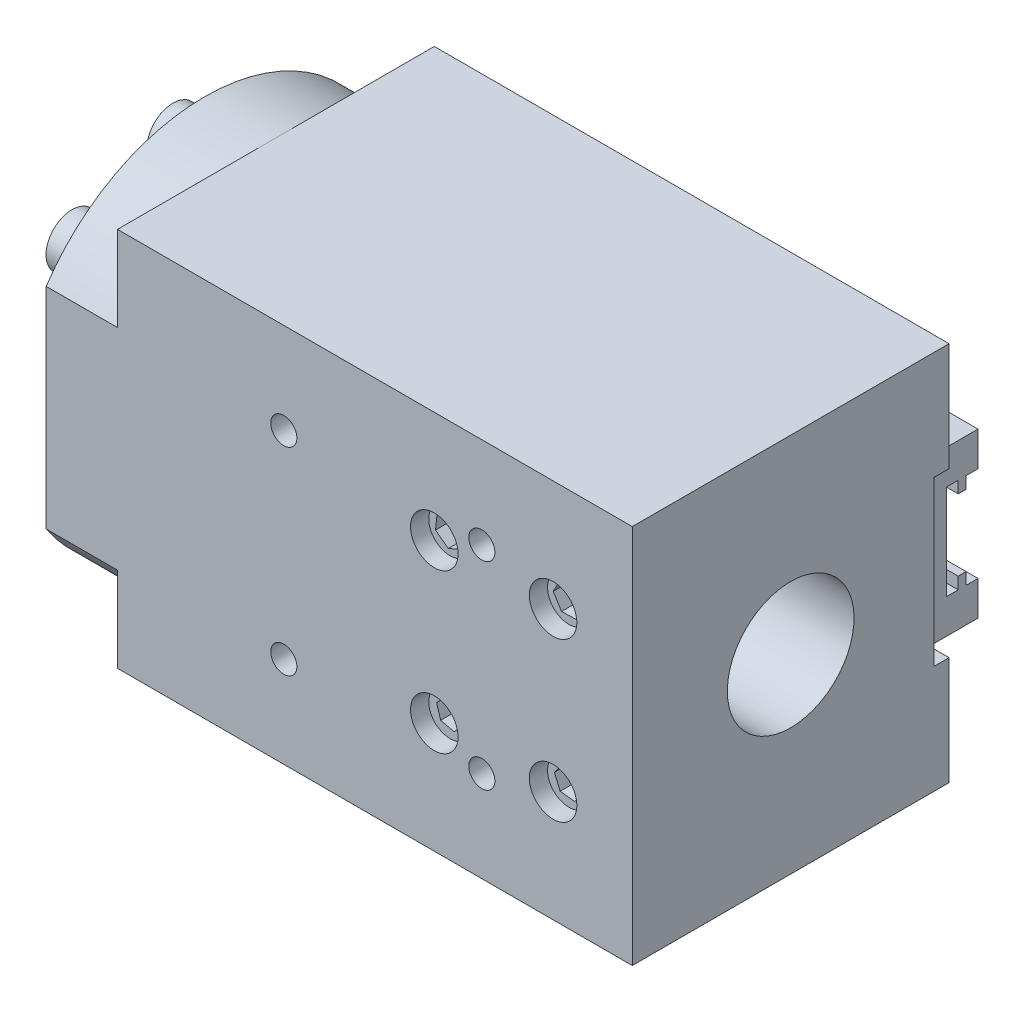
SolidWorks part; units mm, degrees
ref_plane "前视基准面" through (0, 0, 0) normal (0, 0, 1) x (1, 0, 0)
ref_plane "上视基准面" through (0, 0, 0) normal (0, 1, 0) x (1, 0, 0)
ref_plane "右视基准面" through (0, 0, 0) normal (1, 0, 0) x (0, 0, -1)
sketch "草图1" plane through (0, 0, 0) normal (0, 0, 1) x (1, 0, 0)
  line L1 (-32.5, 24) -> (32.5, 24)
  line L2 (-32.5, 24) -> (-32.5, -24)
  line L3 (-32.5, -24) -> (32.5, -24)
  line L4 (32.5, 24) -> (32.5, -24)
  line L5 (-32.5, 24) -> (32.5, -24) construction
  line L6 (-32.5, -24) -> (32.5, 24) construction
  point P0 (0, 0)
  dimension "D1" = 48
  dimension "D2" = 65
extrude "凸台-拉伸1" add sketch "草图1" along normal blind 40
sketch "草图2" plane through (0, 0, 40) normal (0, 0, 1) x (1, 0, 0)
  line L0 (32.5, -24) -> (32.5, 24) construction
  line L1 (32.5, 24) -> (-32.5, 24) construction
  line L2 (-32.5, -24) -> (32.5, -24) construction
  circle A0 centre (22.5, 10) radius 3
  circle A1 centre (22.5, -10) radius 3
  circle A2 centre (7.5, 10) radius 3
  circle A3 centre (7.5, -10) radius 3
  dimension "D1" = 6
  dimension "D2" = 6
  dimension "D3" = 6
  dimension "D4" = 6
  dimension "D5" = 15
  dimension "D6" = 15
  dimension "D7" = 10
  dimension "D8" = 10
  dimension "D9" = 14
  dimension "D10" = 14
  dimension "D11" = 14
  dimension "D12" = 14
extrude "切除-拉伸1" cut sketch "草图2" against normal blind 6
hole_wizard "Ø3.3 (3.3) 直径孔1" positions "草图3" profile "草图4" hole size "Ø3.3" standard "GB"
sketch "草图3" plane through (0, 0, 40) normal (0, 0, 1) x (1, 0, 0)
  line L0 (32.5, -24) -> (32.5, 24) construction
  line L2 (-32.5, -24) -> (32.5, -24) construction
  line L3 (32.5, 24) -> (-32.5, 24) construction
  point P0 (13.5, -12.5)
  point P14 (-11.5, -12.5)
  point P17 (13.5, 12.5)
  point P19 (-11.5, 12.5)
  dimension "D1" = 19
  dimension "D2" = 11.5
  dimension "D3" = 25
  dimension "D4" = 11.5
  dimension "D5" = 11.5
  dimension "D6" = 25
sketch "草图4" plane through (13.5, -12.5, 40) normal (1, 0, 0) x (0, -1, 0)
  line L0 (0, 0) -> (0, 10.9914)
  line L1 (0, 10.9914) -> (1.65, 10)
  line L2 (1.65, 10) -> (1.65, 0)
  line L5 (1.65, 0) -> (0, 0)
  line L10 (0, 10.9914) -> (-1.65, 10) construction
  line L11 (0, -6.35) -> (0, 107.95) construction
  dimension "孔直径" = 3.3
  dimension "孔深度" = 10
  dimension "导头角度" = 118
sketch "草图5" plane through (0, 0, 34) normal (0, 0, 1) x (1, 0, 0)
  circle A0 centre (22.5, 10) radius 2.7
  circle A1 centre (7.5, 10) radius 2.7
  circle A2 centre (7.5, -10) radius 2.7
  circle A3 centre (22.5, -10) radius 2.7
  dimension "D1" = 5.4
  dimension "D2" = 5.4
  dimension "D3" = 5.4
  dimension "D4" = 5.4
extrude "凸台-拉伸2" add sketch "草图5" along normal blind 4
sketch "草图6" plane through (0, 0, 38) normal (0, 0, 1) x (1, 0, 0)
  line L1 (24.3416, -10.211) -> (23.6035, -8.5106)
  line L2 (23.6035, -8.5106) -> (21.7619, -8.2997)
  line L3 (21.7619, -8.2997) -> (20.6584, -9.789)
  line L4 (20.6584, -9.789) -> (21.3965, -11.4894)
  line L5 (21.3965, -11.4894) -> (23.2381, -11.7003)
  line L6 (23.2381, -11.7003) -> (24.3416, -10.211)
  line L7 (5.7948, -9.6064) -> (6.3065, -11.2799)
  line L8 (6.3065, -11.2799) -> (8.0117, -11.6735)
  line L9 (8.0117, -11.6735) -> (9.2052, -10.3936)
  line L10 (9.2052, -10.3936) -> (8.6935, -8.7201)
  line L11 (8.6935, -8.7201) -> (6.9883, -8.3265)
  line L12 (6.9883, -8.3265) -> (5.7948, -9.6064)
  line L13 (21.4504, 11.6821) -> (20.5185, 9.9321)
  line L14 (20.5185, 9.9321) -> (21.5681, 8.25)
  line L15 (21.5681, 8.25) -> (23.5496, 8.3179)
  line L16 (23.5496, 8.3179) -> (24.4815, 10.0679)
  line L17 (24.4815, 10.0679) -> (23.4319, 11.75)
  line L18 (23.4319, 11.75) -> (21.4504, 11.6821)
  line L19 (5.8733, 11.1988) -> (5.6484, 9.1906)
  line L20 (5.6484, 9.1906) -> (7.2752, 7.9918)
  line L21 (7.2752, 7.9918) -> (9.1267, 8.8012)
  line L22 (9.1267, 8.8012) -> (9.3516, 10.8094)
  line L23 (9.3516, 10.8094) -> (7.7248, 12.0082)
  line L24 (7.7248, 12.0082) -> (5.8733, 11.1988)
  circle A0 centre (22.5, -10) radius 1.8536 construction
  circle A1 centre (7.5, -10) radius 1.75 construction
  circle A2 centre (22.5, 10) radius 1.717 construction
  circle A3 centre (7.5, 10) radius 1.75 construction
  dimension "D1" = 3.5
  dimension "D2" = 3.5
extrude "切除-拉伸2" cut sketch "草图6" against normal blind 4
sketch "草图7" plane through (-32.5, 0, 0) normal (-1, 0, 0) x (0, 0, 1)
  line L4 (0, 24) -> (0, -24)
  line L5 (0, -24) -> (40, -24)
  line L6 (40, -24) -> (40, 24)
  line L7 (40, 24) -> (0, 24)
  line L8 (0, 13.2665) -> (0, -13.2665)
  line L10 (40, -13.2665) -> (40, 13.2665)
  arc A0 (40, 13.2665) -> (0, 13.2665) centre (20, 0) ccw
  arc A1 (0, -13.2665) -> (40, -13.2665) centre (20, 0) ccw
  point P4 (0, 0)
  dimension "D1" = 48
  dimension "D3" = 20
  dimension "D2" = 0
extrude "凸台-拉伸3" add sketch "草图7" along normal blind 9
sketch "草图8" plane through (-41.5, 0, 0) normal (-1, 0, 0) x (0, 0, 1)
  line L0 (32.7279, 12.7279) -> (20, 0) construction
  line L1 (20, 18) -> (20, 0) construction
  line L2 (20, 0) -> (7.2721, 12.7279) construction
  circle A0 centre (20, 18) radius 3.3
  circle A1 centre (20, 0) radius 18 construction
  circle A2 centre (32.7279, 12.7279) radius 3.3
  circle A3 centre (7.2721, 12.7279) radius 3.3
  dimension "D1" = 6.6
  dimension "D2" = 36
  dimension "D3" = 6.6
  dimension "D4" = 6.6
  dimension "D5" = 45
  dimension "D6" = 45
extrude "凸台-拉伸4" add sketch "草图8" along normal blind 4
sketch "草图9" plane through (-45.5, 0, 0) normal (-1, 0, 0) x (0, 0, 1)
  line L13 (5.8111, 11.7646) -> (7.3758, 10.981)
  line L14 (7.3758, 10.981) -> (8.8368, 11.9443)
  line L15 (8.8368, 11.9443) -> (8.7331, 13.6912)
  line L16 (8.7331, 13.6912) -> (7.1683, 14.4748)
  line L17 (7.1683, 14.4748) -> (5.7073, 13.5116)
  line L18 (5.7073, 13.5116) -> (5.8111, 11.7646)
  line L19 (31.4869, 11.4941) -> (33.1759, 11.0362)
  line L20 (33.1759, 11.0362) -> (34.417, 12.2701)
  line L21 (34.417, 12.2701) -> (33.969, 13.9617)
  line L22 (33.969, 13.9617) -> (32.2799, 14.4196)
  line L23 (32.2799, 14.4196) -> (31.0389, 13.1858)
  line L24 (31.0389, 13.1858) -> (31.4869, 11.4941)
  line L25 (18.4784, 17.1356) -> (19.9878, 16.25)
  line L26 (19.9878, 16.25) -> (21.5094, 17.1145)
  line L27 (21.5094, 17.1145) -> (21.5216, 18.8644)
  line L28 (21.5216, 18.8644) -> (20.0122, 19.75)
  line L29 (20.0122, 19.75) -> (18.4906, 18.8855)
  line L30 (18.4906, 18.8855) -> (18.4784, 17.1356)
  circle A1 centre (32.7279, 12.7279) radius 1.75 construction
  circle A2 centre (7.2721, 12.7279) radius 1.75 construction
  circle A3 centre (20, 18) radius 1.75 construction
extrude "切除-拉伸3" cut sketch "草图9" against normal blind 4
mirror "镜向1" about plane through (0, 0, 0) normal (0, 1, 0) of "切除-拉伸3", "凸台-拉伸4"
sketch "草图11" plane through (-41.5, 0, 0) normal (-1, 0, 0) x (0, 0, 1)
  circle A0 centre (20, 0) radius 8
  dimension "D1" = 16
extrude "切除-拉伸4" cut sketch "草图11" against normal through all
sketch "草图12" plane through (32.5, 0, 0) normal (1, 0, 0) x (0, 0, -1)
  line L0 (0, -10.335) -> (-1.91, -10.335)
  line L1 (0, -24) -> (0, 24) construction
  line L2 (-1.91, -10.335) -> (-1.91, 10.335)
  line L3 (-1.91, 10.335) -> (0, 10.335)
  line L4 (0, -10.335) -> (0, 10.335)
  point P4 (0, 0)
  dimension "D1" = 1.91
  dimension "D2" = 20.67
  dimension "D3" = 10.335
extrude "切除-拉伸5" cut sketch "草图12" against normal blind 2.5
sketch "草图13" plane through (30, 0, 0) normal (1, 0, 0) x (0, 0, -1)
  line L0 (-1.91, 10.335) -> (6.15, 10.335)
  line L1 (6.15, 10.335) -> (6.15, 5.995)
  line L2 (-1.91, -10.335) -> (6.15, -10.335)
  line L3 (6.15, -10.335) -> (6.15, -5.995)
  line L4 (0, -10.335) -> (0, 10.335)
  line L5 (0, 10.335) -> (-1.91, 10.335)
  line L6 (-1.91, 10.335) -> (-1.91, -10.335)
  line L7 (-1.91, -10.335) -> (0, -10.335)
  line L10 (-1.91, 10.335) -> (-1.91, -10.335)
  line L11 (6.15, -5.995) -> (4.65, -5.995)
  line L12 (4.65, -5.995) -> (4.65, -4.495)
  line L13 (4.65, -4.495) -> (3.65, -4.495)
  line L14 (3.65, -4.495) -> (3.65, -5.995)
  line L15 (3.65, -5.995) -> (2.15, -5.995)
  line L16 (2.15, -5.995) -> (2.15, 5.995)
  line L17 (2.15, 5.995) -> (3.65, 5.995)
  line L18 (3.65, 5.995) -> (3.65, 4.495)
  line L19 (3.65, 4.495) -> (4.65, 4.495)
  line L20 (4.65, 4.495) -> (4.65, 5.995)
  line L21 (4.65, 5.995) -> (6.15, 5.995)
  dimension "D2" = 8.06
  dimension "D3" = 4.34
  dimension "D4" = 4.34
  dimension "D5" = 8.06
  dimension "D6" = 1.5
  dimension "D7" = 1
  dimension "D8" = 1
  dimension "D9" = 1.5
  dimension "D10" = 1.5
  dimension "D11" = 1.5
  dimension "D12" = 1.5
  dimension "D13" = 1.5
  dimension "D14" = 1.5
  dimension "D1" = 0
extrude "凸台-拉伸5" add sketch "草图13" against normal blind 30
